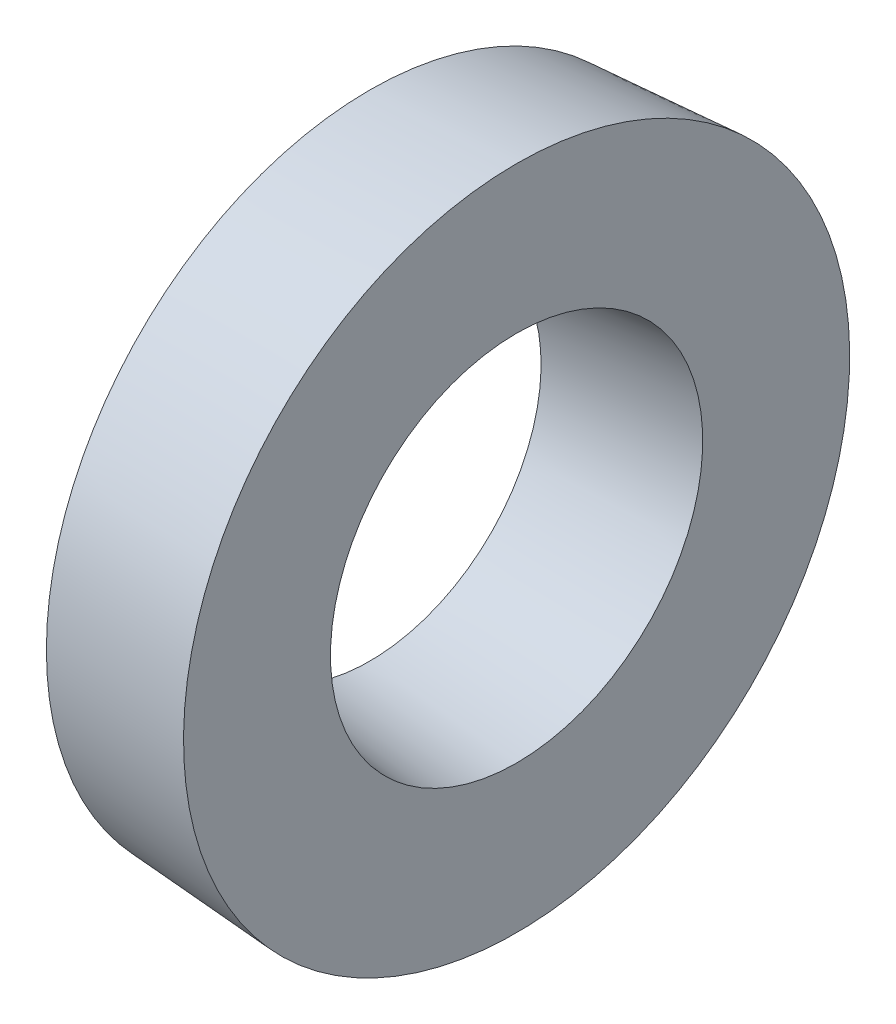
SolidWorks part; units mm, degrees
ref_plane "Front Plane" through (0, 0, 0) normal (0, 0, 1) x (1, 0, 0)
ref_plane "Top Plane" through (0, 0, 0) normal (0, 1, 0) x (1, 0, 0)
ref_plane "Right Plane" through (0, 0, 0) normal (1, 0, 0) x (0, 0, -1)
sketch "Sketch1" plane through (0, 0, 0) normal (0, 0, 1) x (1, 0, 0)
  line L0 (0, 0) -> (5000, 0) construction
  line L1 (3400, 350) -> (3400, 660)
  line L2 (3400, 660) -> (3700, 680)
  line L3 (3700, 680) -> (3700, 380)
  line L4 (3700, 380) -> (3400, 350)
revolve "Revolve1" add sketch "Sketch1" angle 360 about L0
